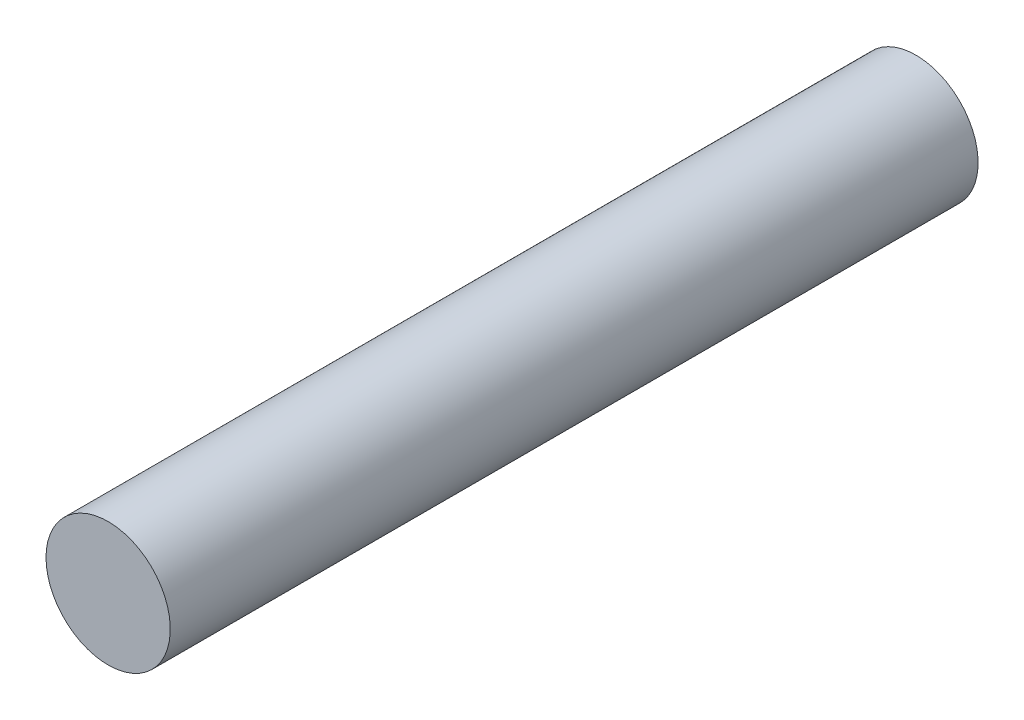
SolidWorks part; units mm, degrees
material "AISI 1020"
ref_plane "Front Plane" through (0, 0, 0) normal (0, 0, 1) x (1, 0, 0)
ref_plane "Top Plane" through (0, 0, 0) normal (0, 1, 0) x (1, 0, 0)
ref_plane "Right Plane" through (0, 0, 0) normal (1, 0, 0) x (0, 0, -1)
sketch "Sketch1" plane through (0, 0, 0) normal (0, 0, 1) x (1, 0, 0)
  circle A0 centre (-50.6257, 32.5477) radius 1
  dimension "D1" = 2
extrude "Boss-Extrude1" add sketch "Sketch1" along normal blind 13
